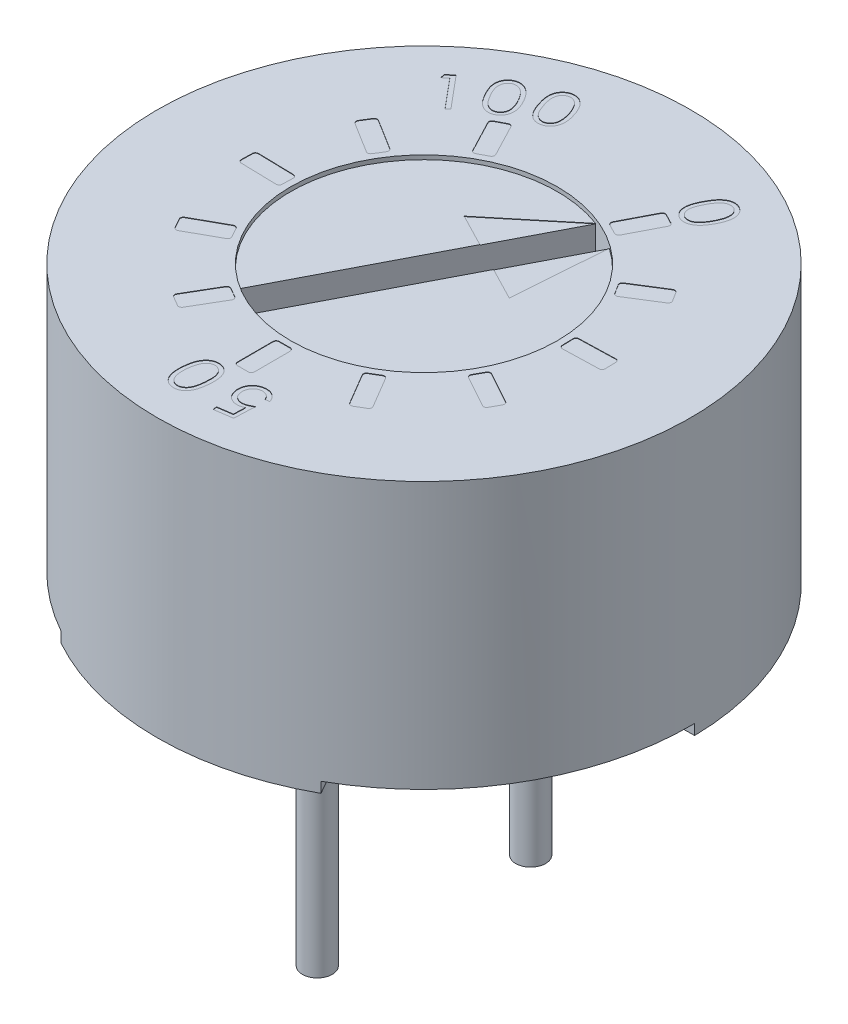
SolidWorks part; units mm, degrees
ref_plane "Front Plane" through (0, 0, 0) normal (0, 0, 1) x (1, 0, 0)
ref_plane "Top Plane" through (0, 0, 0) normal (0, 1, 0) x (1, 0, 0)
ref_plane "Right Plane" through (0, 0, 0) normal (1, 0, 0) x (0, 0, -1)
sketch "Sketch1" plane through (0, 0, 0) normal (0, 1, 0) x (1, 0, 0)
  circle A0 centre (0, 0) radius 6.35
  dimension "D1" = 12.7
extrude "Extrude1" add sketch "Sketch1" along normal blind 6.35
sketch "Sketch2" plane through (0, 6.35, 0) normal (0, 1, 0) x (-1, 0, 0)
  circle A0 centre (0, 0) radius 3.175
  dimension "D1" = 6.35
extrude "Extrude2" cut sketch "Sketch2" against normal blind 0.1
sketch "Sketch3" plane through (0, 6.25, 0) normal (0, 1, 0) x (-1, 0, 0)
  line L0 (1.7877, 2.6239) -> (1.111, 2.9743)
  line L1 (1.7877, 2.6239) -> (-1.111, -2.9743)
  line L2 (1.111, 2.9743) -> (-1.7877, -2.6239)
  line L4 (1.7877, 2.6239) -> (-1.7877, -2.6239) construction
  circle A0 centre (0, 0) radius 3.175 construction
  arc A1 (1.7877, 2.6239) -> (1.111, 2.9743) centre (0, 0) ccw
  arc A2 (-1.7877, -2.6239) -> (-1.111, -2.9743) centre (0, 0) ccw
  circle M1 centre (0, 0) radius 3.175
  dimension "D1" = 0.762
extrude "Extrude3" cut sketch "Sketch3" against normal blind 0.9 contours L1 L4 M1 | L4 L0 L2
sketch "Sketch4" plane through (0, 6.25, 0) normal (0, 1, 0) x (-1, 0, 0)
  line L0 (-1.111, -2.9743) -> (0.6038, -1.5601)
  line L1 (0.6038, -1.5601) -> (-1.6225, -0.4073)
  line L2 (-1.6225, -0.4073) -> (-1.7877, -2.6239)
  line L3 (-1.111, -2.9743) -> (-1.7877, -2.6239)
  line L4 (1.4493, 2.7991) -> (-1.4599, -2.8195) construction
  line L5 (1.7877, 2.6239) -> (1.111, 2.9743) construction
  arc A0 (-1.7877, -2.6239) -> (-1.111, -2.9743) centre (0, 0) ccw construction
extrude "Extrude4" cut sketch "Sketch4" against normal blind 0.01
sketch "Sketch5" plane through (0, 6.35, 0) normal (0, 1, 0) x (-1, 0, 0)
  line L0 (-1.7087, -2.8586) -> (-1.3482, -3.0452)
  line L1 (-1.7087, -2.8586) -> (-2.1672, -3.744)
  line L2 (-1.3482, -3.0452) -> (-1.8067, -3.9306)
  line L3 (-2.1672, -3.744) -> (-1.8067, -3.9306)
  line L4 (0, 0) -> (-1.4599, -2.8195) construction
  arc A0 (-1.7877, -2.6239) -> (-1.111, -2.9743) centre (0, 0) ccw construction
extrude "Extrude5" cut sketch "Sketch5" against normal blind 0.01
fillet "Fillet1" radius 0.075 4 edges at (1.7087, 6.345, -2.8586) (1.3482, 6.345, -3.0452) (2.1672, 6.345, -3.744) (1.8067, 6.345, -3.9306)
pattern_circular "CirPattern1" count 11 every 30.5 about axis through (0, 0, 0) along (0, 1, 0) of "Extrude5", "Fillet1"
sketch "Sketch6" plane through (0, 6.35, 0) normal (0, 1, 0) x (-1, 0, 0)
  circle A0 centre (0, 0) radius 4.5479 construction
  text T0 "0                                                 " font "Century Gothic" height 1
  text T1 "50          " font "Century Gothic" height 1
  text T2 "100                                                " font "Century Gothic" height 1
extrude "Extrude6" cut sketch "Sketch6" against normal blind 0.01
sketch "Sketch7" plane through (0, 0, 0) normal (0, -1, 0) x (1, 0, 0)
  line L0 (3.093, 5.5458) -> (2.5155, 4.5104)
  line L1 (0, 5.1644) -> (0, 7.1975) construction
  line L2 (-3.093, 5.5458) -> (-2.5155, 4.5104)
  line L3 (2.5861, 5.319) -> (2.2582, 4.6445)
  line L4 (-2.5861, 5.319) -> (-2.2582, 4.6445)
  arc A0 (2.5155, 4.5104) -> (2.2582, 4.6445) centre (0, 0) ccw
  circle A1 centre (0, 0) radius 6.35 construction
  arc A2 (3.093, 5.5458) -> (-3.093, 5.5458) centre (0, 0) ccw
  arc A3 (2.5861, 5.319) -> (-2.5861, 5.319) centre (0, 0) ccw
  arc A4 (-2.2582, 4.6445) -> (-2.5155, 4.5104) centre (0, 0) ccw
  arc A5 (2.5155, 4.5104) -> (-2.5155, 4.5104) centre (0, 0) ccw construction
  arc A6 (2.8808, 5.1654) -> (-2.8808, 5.1654) centre (0, 0) ccw construction
  dimension "D1" = 0.75
extrude "Extrude7" add sketch "Sketch7" along normal blind 0.25
pattern_circular "CirPattern2" count 3 over 360 about axis through (0, 0, 0) along (0, 1, 0) of "Extrude7"
sketch "Sketch8" plane through (0, 0, 0) normal (0, -1, 0) x (1, 0, 0)
  circle A0 centre (2.54, 0) radius 0.3555
  circle A1 centre (-2.54, 0) radius 0.3555
  circle A2 centre (0, 2.54) radius 0.3555
  dimension "D1" = 0.711
  dimension "D2" = 0.711
  dimension "D3" = 0.711
  dimension "D4" = 2.54
  dimension "D5" = 2.54
  dimension "D6" = 2.54
extrude "Extrude8" add sketch "Sketch8" along normal blind 4.57
sketch "Sketch9" plane through (0, -4.57, 0) normal (0, -1, 0) x (1, 0, 0)
  circle A1 centre (0, 2.54) radius 0.3555
  circle A2 centre (0, 2.54) radius 0.3555
  dimension "D1" = 0
extrude "Extrude9" add sketch "Sketch9" along normal blind 2.285
